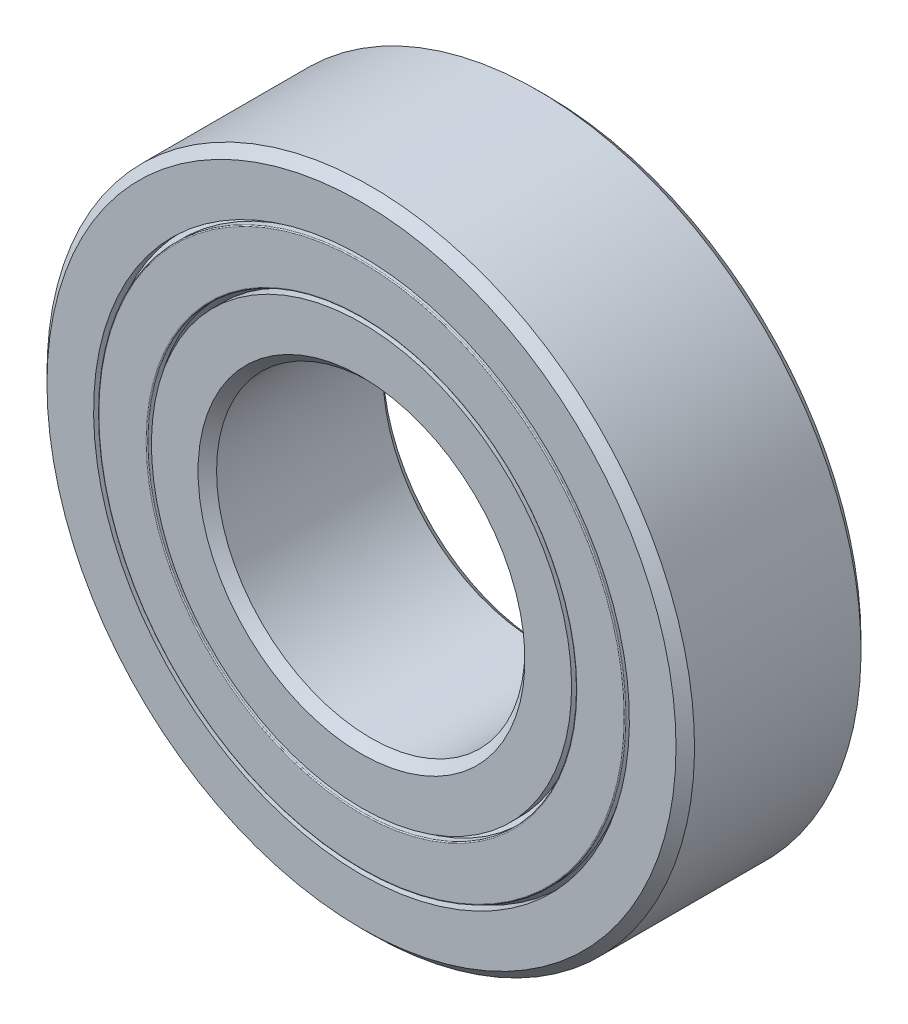
SolidWorks part; units mm, degrees
ref_plane "Front Plane" through (0, 0, 0) normal (0, 0, 1) x (1, 0, 0)
ref_plane "Top Plane" through (0, 0, 0) normal (0, 1, 0) x (1, 0, 0)
ref_plane "Right Plane" through (0, 0, 0) normal (1, 0, 0) x (0, 0, -1)
sketch "Sketch1" plane through (0, 0, 0) normal (0, 0, 1) x (1, 0, 0)
  line L0 (-21, 0) -> (21, 0) construction
  line L1 (-10, 0) -> (10, 0) construction
  circle A0 centre (0, 0) radius 10 construction
  circle A1 centre (0, 0) radius 21 construction
  point P3 (0, 0)
  point P6 (0, 0)
  point P7 (0, -10)
  point P11 (0, -21)
  point P12 (0, 10)
  point P13 (0, 21)
  dimension "OD" = 42
  dimension "ID" = 20
sketch "Sketch2" plane through (0, 0, 0) normal (1, 0, 0) x (0, 0, -1)
  line L0 (-6, 21) -> (6, 21) construction
  line L1 (0, 21) -> (0, -21) construction
  line L2 (5.4, 21) -> (-5.4, 21)
  line L3 (-5.4, 21) -> (-6, 20.4)
  line L4 (-6, 20.4) -> (-6, 17.375)
  line L5 (-6, 17.375) -> (-2.6667, 17.375)
  line L6 (6, 17.375) -> (2.6667, 17.375)
  line L7 (6, 20.4) -> (6, 17.375)
  line L8 (5.4, 21) -> (6, 20.4)
  line L9 (0, 21) -> (0, 15.5) construction
  line L10 (0, 15.5) -> (0, 10) construction
  line L11 (0, 21) -> (0, -21) construction
  line L12 (-6, 0) -> (6, 0) construction
  line L13 (6, 10) -> (-6, 10) construction
  line L14 (0, 18.7599) -> (0, 12.2401) construction
  line L15 (-6, -10) -> (6, -10) construction
  line L16 (-6, 10) -> (-6, -10) construction
  line L17 (6, 21) -> (6, -21) construction
  line L18 (-6, 17.375) -> (-6, 17.1875) construction
  line L19 (-6, 17.1875) -> (-6, 17) construction
  line L20 (-6, 17) -> (-6, 16.8125) construction
  line L21 (-6, 16.8125) -> (-6, 16.625) construction
  line L22 (-6, 16.625) -> (-6, 16.4375) construction
  line L24 (-4.3333, 17.375) -> (-4.3333, 15.5) construction
  arc A0 (-2.6667, 17.375) -> (2.6667, 17.375) centre (0, 15.5) cw
  circle A1 centre (0, 15.5) radius 3.2599 construction
  point P14 (0, 10)
  point P17 (0, 0)
  point P21 (0, 21)
  point P29 (0, 10)
  point P30 (0, -10)
  point P46 (-4.3333, 16.4375)
  dimension "Width" = 12
  dimension "D1" = 45
  dimension "D2" = 0.6
  dimension "D3" = 5.3333
  dimension "D4" = 1.875
  dimension "For Shaft Diameter" = 20
  dimension "For Housing ID" = 42
sketch "Sketch3" plane through (0, 0, 0) normal (1, 0, 0) x (0, 0, -1)
  line L0 (5.4, 21) -> (6, 20.4) construction
  line L1 (6, 20.4) -> (6, 17.375) construction
  line L2 (6, 17.375) -> (2.6667, 17.375) construction
  line L3 (-6, 17.375) -> (-2.6667, 17.375) construction
  line L4 (-6, 20.4) -> (-6, 17.375) construction
  line L5 (-5.4, 21) -> (-6, 20.4) construction
  line L6 (5.4, 21) -> (-5.4, 21) construction
  line L7 (5.4, 21) -> (6, 20.4)
  line L8 (6, 20.4) -> (6, 17.375)
  line L9 (6, 17.375) -> (2.6667, 17.375)
  line L10 (-6, 17.375) -> (-2.6667, 17.375)
  line L11 (-6, 20.4) -> (-6, 17.375)
  line L12 (-5.4, 21) -> (-6, 20.4)
  line L13 (5.4, 21) -> (-5.4, 21)
  arc A0 (2.6667, 17.375) -> (-2.6667, 17.375) centre (0, 15.5) ccw construction
  arc A1 (2.6667, 17.375) -> (-2.6667, 17.375) centre (0, 15.5) ccw
revolve "Revolve1" add sketch "Sketch3" angle 360 about L12
sketch "Sketch4" plane through (0, 0, 0) normal (1, 0, 0) x (0, 0, -1)
  line L0 (0, 21) -> (0, -21) construction
  line L1 (0, 21) -> (0, -21) construction
  line L2 (-5.4, 10) -> (-6, 10.6)
  line L3 (-6, 10.6) -> (-6, 13.625)
  line L5 (-6, 13.625) -> (-2.6667, 13.625)
  line L6 (-5.4, 10) -> (5.4, 10)
  line L8 (5.4, 10) -> (6, 10.6)
  line L10 (6, 10.6) -> (6, 13.625)
  line L11 (6, 13.625) -> (2.6667, 13.625)
  line L12 (-6, 20.4) -> (-6, 17.375) construction
  line L13 (5.4, 21) -> (6, 20.4) construction
  line L15 (6, -20.4) -> (6, 20.4) construction
  line L16 (5.4, 21) -> (5.4, -21) construction
  arc A1 (2.6667, 13.625) -> (-2.6667, 13.625) centre (0, 15.5) cw
  circle A2 centre (0, 15.5) radius 3.2599 construction
  point P1 (0, 10)
revolve "Revolve2" add sketch "Sketch4" angle 360 about L12
sketch "Sketch5" plane through (0, 0, 0) normal (1, 0, 0) x (0, 0, -1)
  line L0 (-3.2599, 15.5) -> (3.2599, 15.5)
  arc A2 (-3.2599, 15.5) -> (3.2599, 15.5) centre (0, 15.5) cw
  arc A3 (2.6667, 17.375) -> (-2.6667, 17.375) centre (0, 15.5) ccw construction
revolve "Revolve3" add sketch "Sketch5" angle 360 about L0
sketch "Sketch6" plane through (0, 0, 0) normal (1, 0, 0) x (0, 0, -1)
  line L0 (-6, 17.375) -> (-6, 16.4375) construction
  line L1 (-6, 20.4) -> (-6, -20.4) construction
  line L2 (-6, 16.4375) -> (-6, 15.5) construction
  line L3 (-6, 15.5) -> (-6, 14.5625) construction
  line L4 (-6, 14.5625) -> (-6, 13.625) construction
  line L5 (-6, 16.4375) -> (-5.5204, 16.4375) construction
  line L7 (-3.1222, 16.4375) -> (-3.1222, 14.5625) construction
  line L8 (-5.5204, 16.4375) -> (-5.0407, 16.4375) construction
  line L10 (0, 21) -> (0, -21) construction
  line L11 (0, 21) -> (0, -21) construction
  line L12 (-5.0407, 16.4375) -> (-4.5611, 16.4375) construction
  line L13 (-4.5611, 16.4375) -> (-4.0814, 16.4375) construction
  line L14 (-4.0814, 16.4375) -> (-3.6018, 16.4375) construction
  line L15 (-3.6018, 16.4375) -> (-3.1222, 16.4375) construction
  line L16 (-3.1222, 16.4375) -> (-3.6018, 16.4375)
  line L17 (-3.6018, 14.5625) -> (-4.0814, 14.5625) construction
  line L18 (-3.6018, 14.5625) -> (-3.1222, 14.5625)
  line L19 (-4.0814, 14.5625) -> (-4.0814, 16.4375) construction
  line L20 (-3.8416, 16.4375) -> (-3.8416, 14.5625) construction
  circle A0 centre (0, 15.5) radius 3.2599 construction
  circle A1 centre (0, 15.5) radius 3.2599 construction
  arc A2 (-3.6018, 16.4375) -> (-3.6018, 14.5625) centre (-1.8893, 15.5) ccw
  arc A3 (-3.1222, 16.4375) -> (-3.1222, 14.5625) centre (0, 15.5) ccw
  point P28 (-3.8416, 15.5)
revolve "Revolve4" add sketch "Sketch6" angle 360 about L11
pattern_circular "CirPattern1" count 9 over 360 about axis through (0, 0, 0) along (0, 0, 1) of bodies 134 104
sketch "Sketch7" plane through (0, 0, 0) normal (0, 0, 1) x (1, 0, 0)
  line L0 (0, 13.625) -> (0, 14.25) construction
  line L1 (0, 12.2401) -> (0, 18.7599) construction
  line L2 (0, 14.25) -> (0, 14.875) construction
  line L3 (0, 14.875) -> (0, 15.5) construction
  line L4 (0, 15.5) -> (0, 16.125) construction
  line L5 (0, 16.125) -> (0, 16.75) construction
  line L6 (0, 16.75) -> (0, 17.375) construction
  line L7 (0, 20.4) -> (0, 17.375) construction
  line L8 (0, 21) -> (0, -21) construction
  circle A0 centre (0, 0) radius 13.625 construction
  circle A1 centre (0, 0) radius 15.5
  circle A2 centre (0, 0) radius 16.4375
  point P19 (0, 16.4375)
extrude "Boss-Extrude1" add sketch "Sketch7" along normal mid plane 2 separate body
sketch "Sketch8" plane through (0, 0, 0) normal (1, 0, 0) x (0, 0, -1)
  line L0 (-6, 17.1875) -> (-6, 17) construction
  line L1 (-6, 17.0937) -> (-5.5556, 17.0937)
  line L2 (-6, 17.0937) -> (-6, 13.9062)
  line L3 (-6, 13.9062) -> (-5.5556, 13.9062)
  line L4 (-5.3333, 17.0937) -> (-5.3333, 13.9062)
  line L5 (0, 21) -> (0, 15.5) construction
  line L10 (-5.5556, 17.0937) -> (-5.3333, 17.375)
  line L11 (-6, 17.375) -> (-2.6667, 17.375) construction
  line L12 (-5.3333, 17.375) -> (-5.3333, 17.0937)
  line L13 (-5.5556, 13.9062) -> (-5.3333, 13.625)
  line L14 (-5.3333, 13.625) -> (-5.3333, 13.9062)
  line L15 (-6, 17.375) -> (-5.7778, 17.375) construction
  line L16 (6, 17.0937) -> (6, 13.9062)
  line L17 (6, 13.9062) -> (5.5556, 13.9062)
  line L18 (5.5556, 13.9062) -> (5.3333, 13.625)
  line L19 (5.3333, 13.625) -> (5.3333, 13.9062)
  line L20 (5.3333, 17.0937) -> (5.3333, 13.9062)
  line L21 (5.3333, 17.375) -> (5.3333, 17.0937)
  line L22 (5.5556, 17.0937) -> (5.3333, 17.375)
  line L23 (6, 17.0937) -> (5.5556, 17.0937)
  line L24 (-5.7778, 17.375) -> (-5.5556, 17.375) construction
  line L25 (-5.5556, 17.375) -> (-5.3333, 17.375) construction
  line L27 (-6, 13.625) -> (-2.6667, 13.625) construction
  point P23 (-6, 17.0937)
  dimension "D1" = 0.6667
revolve "Revolve5" add sketch "Sketch8" angle 360 about L12
fillet "Fillet1" radius 0.0667 2 edges at (0, -17.0937, 6) (0, -13.9062, 6)
fillet "Fillet2" radius 0.0667 2 edges at (0, -13.9062, -6) (0, -17.0937, -6)
equation "\"D2@Sketch2\" = \"Width@Sketch2\" * .05"
equation "\"D3@Sketch2\" = \"Width@Sketch2\" / 2.25"
equation "\"D4@Sketch2\"=( \"OD@Sketch1\" - \"Width@Sketch2\" )  *.5*.125"
equation "\"D1@Boss-Extrude1\" = \"Width@Sketch2\" / 6"
equation "\"D1@Sketch8\"=(\"Width@Sketch2\"-\"D3@Sketch2\")*.5*.2"
equation "\"D1@Fillet1\"=\"d1@sketch8\"*.1"
equation "\"D1@Fillet2\"=\"d1@fillet1\""
